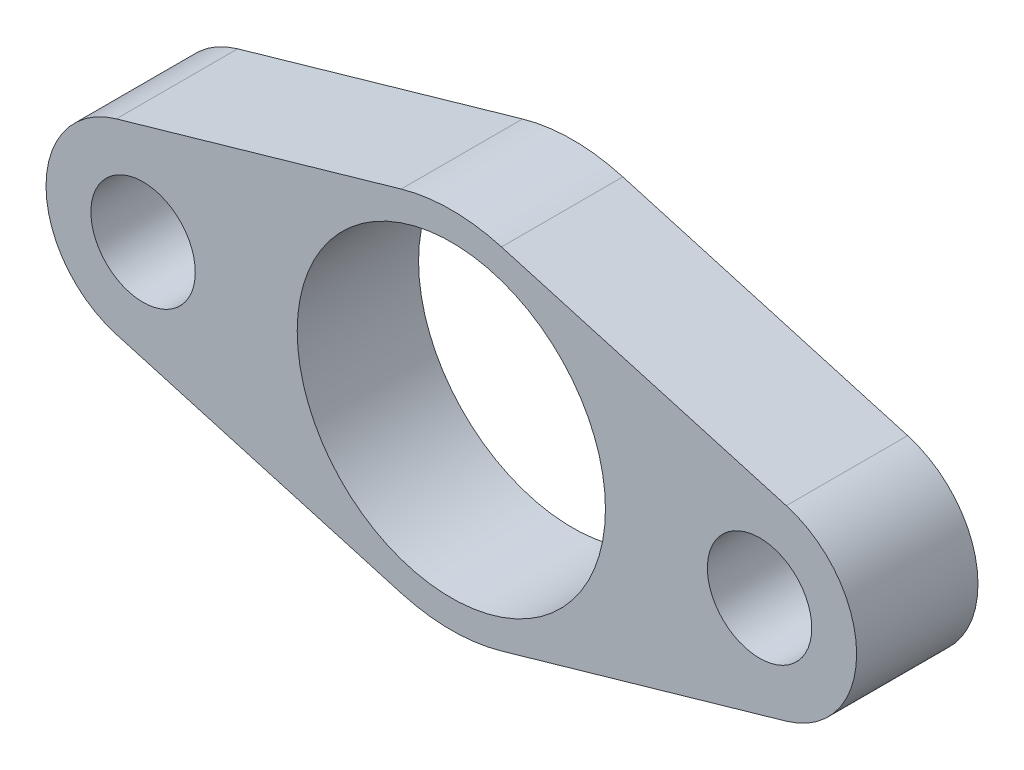
SolidWorks part; units mm, degrees
ref_plane "Front Plane" through (0, 0, 0) normal (0, 0, 1) x (1, 0, 0)
ref_plane "Top Plane" through (0, 0, 0) normal (0, 1, 0) x (1, 0, 0)
ref_plane "Right Plane" through (0, 0, 0) normal (1, 0, 0) x (0, 0, -1)
sketch "Sketch1" plane through (0, 0, 0) normal (0, 0, 1) x (1, 0, 0)
  line L0 (-13.8024, 3.8451) -> (-2.0669, 7.2096)
  line L1 (2.0669, 7.2096) -> (13.8024, 3.8451)
  line L2 (-13.8024, -3.8451) -> (-2.0669, -7.2096)
  line L3 (13.8024, -3.8451) -> (2.0669, -7.2096)
  circle A0 centre (0, 0) radius 6.35
  circle A1 centre (12.7, 0) radius 2.15
  circle A2 centre (-12.7, 0) radius 2.15
  arc A3 (-13.8024, 3.8451) -> (-13.8024, -3.8451) centre (-12.7, 0) ccw
  arc A4 (13.8024, -3.8451) -> (13.8024, 3.8451) centre (12.7, 0) ccw
  arc A5 (-2.0669, -7.2096) -> (2.0669, -7.2096) centre (0, 0) ccw
  arc A6 (2.0669, 7.2096) -> (-2.0669, 7.2096) centre (0, 0) ccw
  dimension "D1" = 12.7
  dimension "D2" = 4.3
  dimension "D3" = 4.3
  dimension "D6" = 15
  dimension "D7" = 8
  dimension "D8" = 8
  dimension "D4" = 12.7
  dimension "D5" = 12.7
extrude "Boss-Extrude1" add sketch "Sketch1" along normal blind 5 contours L1 A6 L0 A3 L2 A5 L3 A4 A0 A1 A2
